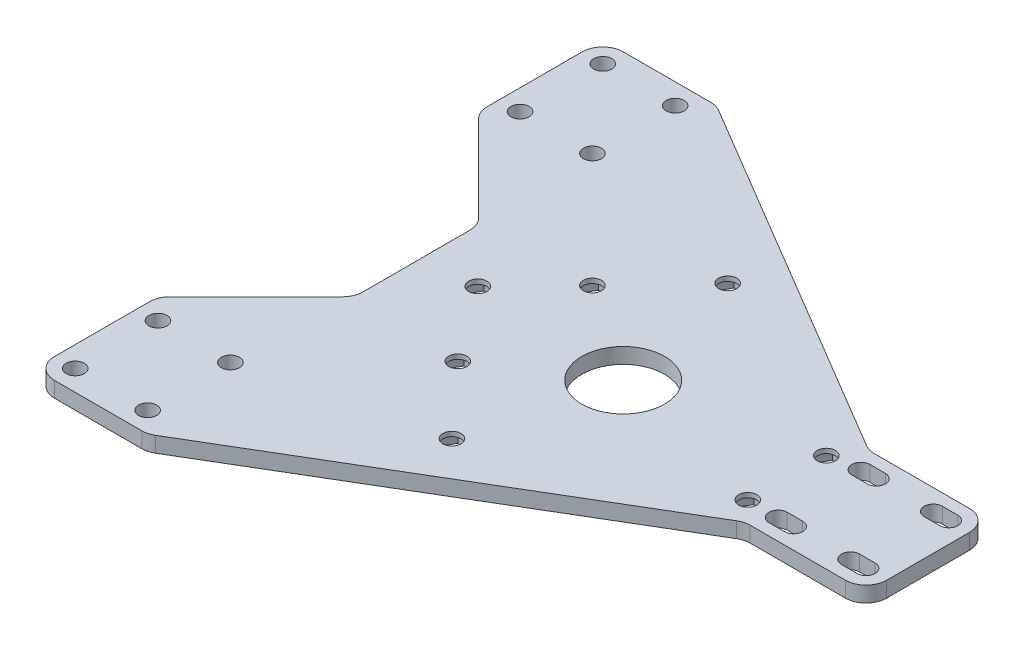
SolidWorks part; units mm, degrees
material "6061-O (SS)"
ref_plane "Plan de face" through (0, 0, 0) normal (0, 0, 1) x (1, 0, 0)
ref_plane "Plan de dessus" through (0, 0, 0) normal (0, 1, 0) x (1, 0, 0)
ref_plane "Plan de droite" through (0, 0, 0) normal (1, 0, 0) x (0, 0, -1)
sketch "Esquisse1" plane through (0, 0, 0) normal (0, 1, 0) x (1, 0, 0)
  line L1 (58.95, -55) -> (-58.95, -55)
  line L2 (58.95, -55) -> (58.95, 55)
  line L3 (58.95, 55) -> (-58.95, 55)
  line L4 (-58.95, -55) -> (-58.95, 55)
  line L5 (58.95, -55) -> (-58.95, 55) construction
  line L6 (58.95, 55) -> (-58.95, -55) construction
  point P0 (0, 0)
  dimension "D1" = 110
  dimension "D2" = 117.9
extrude "Boss.-Extru.1" add sketch "Esquisse1" along normal blind 3
sketch "Esquisse2" plane through (0, 0, 0) normal (0, 1, 0) x (1, 0, 0)
  line L0 (-58.95, -55) -> (58.95, -55) construction
  line L1 (-54.95, -35) -> (-40.95, -35) construction
  line L2 (-54.95, -35) -> (-54.95, -51) construction
  line L3 (-54.95, -51) -> (-40.95, -51) construction
  line L4 (-40.95, -35) -> (-40.95, -51) construction
  line L5 (-54.95, -35) -> (-40.95, -51) construction
  line L6 (-54.95, -51) -> (-40.95, -35) construction
  line L7 (-58.95, 55) -> (-58.95, -55) construction
  line L8 (0, 0) -> (-58.95, 0) construction
  line L9 (-54.95, 51) -> (-40.95, 35) construction
  line L10 (-54.95, 35) -> (-40.95, 51) construction
  line L11 (-40.95, 35) -> (-40.95, 51) construction
  line L12 (-54.95, 51) -> (-40.95, 51) construction
  line L13 (-54.95, 35) -> (-54.95, 51) construction
  line L14 (-54.95, 35) -> (-40.95, 35) construction
  line L15 (46.45, 0) -> (53.45, 8) construction
  line L16 (39.45, 8) -> (53.45, 8) construction
  line L17 (39.45, 8) -> (39.45, -8) construction
  line L18 (39.45, -8) -> (53.45, -8) construction
  line L19 (53.45, 8) -> (53.45, -8) construction
  line L20 (39.45, 8) -> (46.45, 0) construction
  line L21 (39.45, -8) -> (46.45, 0) construction
  line L22 (46.45, 0) -> (53.45, -8) construction
  line L23 (0, 0) -> (58.95, 0) construction
  line L24 (58.95, -55) -> (58.95, 55) construction
  line L25 (58.95, 12) -> (35.45, 12)
  line L26 (35.45, 12) -> (-36.95, 55)
  line L27 (58.95, 55) -> (-58.95, 55) construction
  line L28 (-36.95, 55) -> (58.95, 55)
  line L29 (58.95, 55) -> (58.95, 12)
  line L30 (58.95, -12) -> (35.45, -12)
  line L31 (58.95, -55) -> (58.95, -12)
  line L32 (-36.95, -55) -> (58.95, -55)
  line L33 (35.45, -12) -> (-36.95, -55)
  line L34 (-58.95, -31) -> (-39.95, -12)
  line L35 (-39.95, -12) -> (-39.95, 12)
  line L36 (-39.95, 12) -> (-58.95, 31)
  line L37 (-58.95, 31) -> (-58.95, -31)
  line L38 (37.95, 8) -> (40.95, 8) construction
  line L39 (37.95, 9.75) -> (40.95, 9.75)
  line L40 (37.95, 6.25) -> (40.95, 6.25)
  line L41 (54.95, 8) -> (51.95, 8) construction
  line L42 (54.95, 6.25) -> (51.95, 6.25)
  line L43 (54.95, 9.75) -> (51.95, 9.75)
  line L44 (37.95, -8) -> (40.95, -8) construction
  line L45 (37.95, -6.25) -> (40.95, -6.25)
  line L46 (37.95, -9.75) -> (40.95, -9.75)
  line L47 (54.95, -8) -> (51.95, -8) construction
  line L48 (54.95, -9.75) -> (51.95, -9.75)
  line L49 (54.95, -6.25) -> (51.95, -6.25)
  circle A0 centre (-40.95, -35) radius 1.75
  circle A1 centre (-54.95, -35) radius 1.75
  circle A2 centre (-54.95, -51) radius 1.75
  circle A3 centre (-40.95, -51) radius 1.75
  circle A4 centre (-40.95, 51) radius 1.75
  circle A5 centre (-54.95, 51) radius 1.75
  circle A6 centre (-54.95, 35) radius 1.75
  circle A7 centre (-40.95, 35) radius 1.75
  arc A12 (37.95, 9.75) -> (37.95, 6.25) centre (37.95, 8) ccw
  arc A13 (40.95, 6.25) -> (40.95, 9.75) centre (40.95, 8) ccw
  arc A14 (54.95, 6.25) -> (54.95, 9.75) centre (54.95, 8) ccw
  arc A15 (51.95, 9.75) -> (51.95, 6.25) centre (51.95, 8) ccw
  arc A16 (37.95, -6.25) -> (37.95, -9.75) centre (37.95, -8) ccw
  arc A17 (40.95, -9.75) -> (40.95, -6.25) centre (40.95, -8) ccw
  arc A18 (54.95, -9.75) -> (54.95, -6.25) centre (54.95, -8) ccw
  arc A19 (51.95, -6.25) -> (51.95, -9.75) centre (51.95, -8) ccw
  point P0 (-47.95, -43)
  point P25 (-47.95, 43)
  point P26 (46.45, 0)
  point P33 (39.45, 8)
  point P52 (-39.95, 0)
  point P58 (53.45, 8)
  point P65 (39.45, -8)
  point P72 (53.45, -8)
  dimension "D3" = 3.5
  dimension "D4" = 4
  dimension "D5" = 4
  dimension "D6" = 1.75
  dimension "D1" = 16
  dimension "D2" = 14
  dimension "D7" = 14
  dimension "D8" = 16
  dimension "D9" = 5.5
  dimension "D10" = 4
  dimension "D11" = 4
  dimension "D12" = 4
  dimension "D13" = 4
  dimension "D14" = 4
  dimension "D15" = 4
  dimension "D16" = 1
  dimension "D17" = 1.5
extrude "Enlèv. mat.-Extru.1" cut sketch "Esquisse2" along normal through all
fillet "Congé1" radius 4 12 edges at (35.45, 1.5, 12) (58.95, 1.5, 12) (58.95, 1.5, -12) (35.45, 1.5, -12) (-36.95, 1.5, -55) (-58.95, 1.5, -55) (-58.95, 1.5, -31) (-39.95, 1.5, -12) (-39.95, 1.5, 12) (-58.95, 1.5, 31) (-58.95, 1.5, 55) (-36.95, 1.5, 55)
sketch "Esquisse3" plane through (0, 0, 0) normal (0, 1, 0) x (1, 0, 0)
  line L1 (11, -11) -> (-11, -11) construction
  line L2 (11, -11) -> (11, 11) construction
  line L3 (11, 11) -> (-11, 11) construction
  line L4 (-11, -11) -> (-11, 11) construction
  line L5 (11, -11) -> (-11, 11) construction
  line L6 (11, 11) -> (-11, -11) construction
  line L7 (-11.5, 11) -> (-10.5, 11) construction
  line L8 (-11.5, 13) -> (-10.5, 13)
  line L9 (-11.5, 9) -> (-10.5, 9)
  line L10 (0, 0) -> (-11, 0) construction
  line L11 (0, 0) -> (0, 11) construction
  line L12 (11.5, 11) -> (10.5, 11) construction
  line L13 (11.5, 13) -> (10.5, 13)
  line L14 (11.5, 9) -> (10.5, 9)
  line L15 (11.5, -11) -> (10.5, -11) construction
  line L16 (11.5, -13) -> (10.5, -13)
  line L17 (11.5, -9) -> (10.5, -9)
  line L18 (-11.5, -11) -> (-10.5, -11) construction
  line L19 (-11.5, -13) -> (-10.5, -13)
  line L20 (-11.5, -9) -> (-10.5, -9)
  arc A4 (-11.5, 13) -> (-11.5, 9) centre (-11.5, 11) ccw
  arc A5 (-10.5, 9) -> (-10.5, 13) centre (-10.5, 11) ccw
  arc A6 (11.5, 13) -> (11.5, 9) centre (11.5, 11) cw
  arc A7 (10.5, 9) -> (10.5, 13) centre (10.5, 11) cw
  arc A8 (11.5, -13) -> (11.5, -9) centre (11.5, -11) ccw
  arc A9 (10.5, -9) -> (10.5, -13) centre (10.5, -11) ccw
  arc A10 (-11.5, -13) -> (-11.5, -9) centre (-11.5, -11) cw
  arc A11 (-10.5, -9) -> (-10.5, -13) centre (-10.5, -11) cw
  circle A12 centre (0, 0) radius 8
  point P0 (0, 0)
  point P8 (-11, 11)
  point P22 (11, 11)
  point P29 (11, -11)
  point P36 (-11, -11)
  dimension "D3" = 2
  dimension "D6" = 16
  dimension "D1" = 22
  dimension "D2" = 22
  dimension "D5" = 0.5
extrude "Enlèv. mat.-Extru.2" cut sketch "Esquisse3" along normal through all contours A12
sketch "Esquisse6" plane through (0, 0, 0) normal (0, -1, 0) x (1, 0, 0)
  line L1 (-15.6093, -12.8835) -> (-17.2259, -10.0835)
  line L2 (-17.2259, -10.0835) -> (-20.459, -10.0835)
  line L3 (-20.459, -10.0835) -> (-22.0756, -12.8835)
  line L4 (-22.0756, -12.8835) -> (-20.459, -15.6835)
  line L5 (-20.459, -15.6835) -> (-17.2259, -15.6835)
  line L6 (-17.2259, -15.6835) -> (-15.6093, -12.8835)
  line L7 (-26.5485, -1.6676) -> (-28.1651, 1.1324)
  line L8 (-28.1651, 1.1324) -> (-31.3983, 1.1324)
  line L9 (-31.3983, 1.1324) -> (-33.0149, -1.6676)
  line L10 (-33.0149, -1.6676) -> (-31.3983, -4.4676)
  line L11 (-31.3983, -4.4676) -> (-28.1651, -4.4676)
  line L12 (-28.1651, -4.4676) -> (-26.5485, -1.6676)
  line L13 (-15.9264, 12.8146) -> (-17.543, 15.6146)
  line L14 (-17.543, 15.6146) -> (-20.7762, 15.6146)
  line L15 (-20.7762, 15.6146) -> (-22.3927, 12.8146)
  line L16 (-22.3927, 12.8146) -> (-20.7762, 10.0146)
  line L17 (-20.7762, 10.0146) -> (-17.543, 10.0146)
  line L18 (-17.543, 10.0146) -> (-15.9264, 12.8146)
  line L19 (-3.5419, 26.3319) -> (-5.1584, 29.1319)
  line L20 (-5.1584, 29.1319) -> (-8.3916, 29.1319)
  line L21 (-8.3916, 29.1319) -> (-10.0082, 26.3319)
  line L22 (-10.0082, 26.3319) -> (-8.3916, 23.5319)
  line L23 (-8.3916, 23.5319) -> (-5.1584, 23.5319)
  line L24 (-5.1584, 23.5319) -> (-3.5419, 26.3319)
  line L25 (35.3063, 7.983) -> (33.6898, 10.783)
  line L26 (33.6898, 10.783) -> (30.4566, 10.783)
  line L27 (30.4566, 10.783) -> (28.84, 7.983)
  line L28 (28.84, 7.983) -> (30.4566, 5.183)
  line L29 (30.4566, 5.183) -> (33.6898, 5.183)
  line L30 (33.6898, 5.183) -> (35.3063, 7.983)
  line L31 (35.4914, -7.0159) -> (33.8748, -4.2159)
  line L32 (33.8748, -4.2159) -> (30.6417, -4.2159)
  line L33 (30.6417, -4.2159) -> (29.0251, -7.0159)
  line L34 (29.0251, -7.0159) -> (30.6417, -9.8159)
  line L35 (30.6417, -9.8159) -> (33.8748, -9.8159)
  line L36 (33.8748, -9.8159) -> (35.4914, -7.0159)
  line L37 (-2.8921, -26.3179) -> (-4.5087, -23.5179)
  line L38 (-4.5087, -23.5179) -> (-7.7419, -23.5179)
  line L39 (-7.7419, -23.5179) -> (-9.3584, -26.3179)
  line L40 (-9.3584, -26.3179) -> (-7.7419, -29.1179)
  line L41 (-7.7419, -29.1179) -> (-4.5087, -29.1179)
  line L42 (-4.5087, -29.1179) -> (-2.8921, -26.3179)
  circle A0 centre (32.2583, -7.0159) radius 1.65 construction
  circle A1 centre (32.0732, 7.983) radius 1.65 construction
  circle A2 centre (-6.775, 26.3319) radius 1.65 construction
  circle A3 centre (-6.1253, -26.3179) radius 1.65 construction
  circle A4 centre (-18.8425, -12.8835) radius 1.65 construction
  circle A5 centre (-19.1596, 12.8146) radius 1.65 construction
  circle A6 centre (-29.7817, -1.6676) radius 1.65 construction
  circle A7 centre (-18.8425, -12.8835) radius 2.8 construction
  circle A8 centre (-29.7817, -1.6676) radius 2.8 construction
  circle A9 centre (-19.1596, 12.8146) radius 2.8 construction
  circle A10 centre (-6.775, 26.3319) radius 2.8 construction
  circle A11 centre (32.0732, 7.983) radius 2.8 construction
  circle A12 centre (32.2583, -7.0159) radius 2.8 construction
  circle A13 centre (-6.1253, -26.3179) radius 2.8 construction
  dimension "D1" = 3.3
  dimension "D2" = 5.6
extrude "Enlèv. mat.-Extru.3" cut sketch "Esquisse6" against normal blind 2.1
sketch "Esquisse19" plane through (0, 0, 0) normal (0, -1, 0) x (1, 0, 0)
  circle A0 centre (-19.1596, 12.8146) radius 3.2332 construction
  circle A1 centre (-6.775, 26.3319) radius 3.2332 construction
  circle A2 centre (-29.7817, -1.6676) radius 3.2332 construction
  circle A3 centre (-18.8425, -12.8835) radius 3.2332 construction
  circle A4 centre (-6.1253, -26.3179) radius 3.2332 construction
  circle A5 centre (32.2583, -7.0159) radius 3.2332 construction
  circle A6 centre (32.0732, 7.983) radius 3.2332 construction
  circle A7 centre (-29.7817, -1.6676) radius 1.75
  circle A8 centre (-19.1596, 12.8146) radius 1.75
  circle A9 centre (-6.775, 26.3319) radius 1.75
  circle A10 centre (-18.8425, -12.8835) radius 1.75
  circle A11 centre (-6.1253, -26.3179) radius 1.75
  circle A12 centre (32.2583, -7.0159) radius 1.75
  circle A13 centre (32.0732, 7.983) radius 1.75
  dimension "D1" = 3.5
extrude "Enlèv. mat.-Extru.4" cut sketch "Esquisse19" against normal through all
